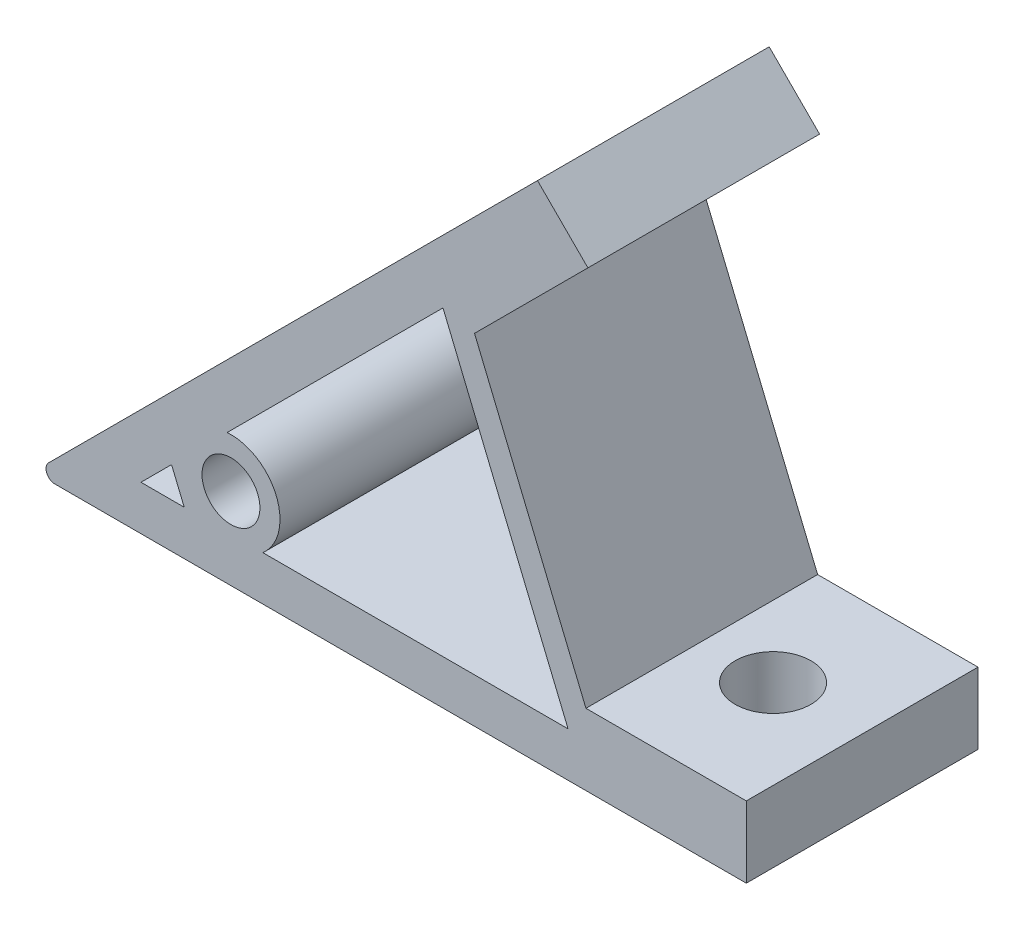
SolidWorks part; units mm, degrees
ref_plane "前视基准面" through (0, 0, 0) normal (0, 0, 1) x (1, 0, 0)
ref_plane "上视基准面" through (0, 0, 0) normal (0, 1, 0) x (1, 0, 0)
ref_plane "右视基准面" through (0, 0, 0) normal (1, 0, 0) x (0, 0, -1)
sketch "草图1" plane through (0, 0, 0) normal (0, 0, 1) x (1, 0, 0)
  line B0 (-77.5858, 0) -> (0, 0)
  line B1 (-67.9289, 5) -> (-63.0745, 5)
  line B2 (-54.2575, 5) -> (-20, 5)
  line B3 (-17.9955, 8) -> (0, 8)
  line B4 (-78.2929, 1.7071) -> (-23.4315, 56.5685)
  line B5 (-67.9289, 5) -> (-64.4963, 8.4326)
  line B6 (-58.2617, 14.6672) -> (-34.0381, 38.8909)
  line B7 (-30.4993, 38.187) -> (-17.7746, 50.9117)
  line B8 (0, 0) -> (0, 8)
  line B9 (-17.7746, 50.9117) -> (-23.4315, 56.5685)
  line B10 (-20, 5) -> (-34.0381, 38.8909)
  line B11 (-17.9955, 8) -> (-30.4993, 38.187)
  line B12 (-63.0745, 5) -> (-64.4963, 8.4326)
  arc B13 (-78.2929, 1.7071) -> (-77.5858, 0) centre (-77.5858, 1) ccw
  circle B14 centre (-57.8269, 9.1844) radius 3.25
  arc B15 (-54.2575, 5) -> (-58.2617, 14.6672) centre (-57.8269, 9.1844) ccw
sketch_block_instance "A$C18907C9D-1"
sketch_block "A$C18907C9D"
extrude "凸台-拉伸1" add sketch "草图1" along normal mid plane 26
sketch "草图3" plane through (0, 8, 0) normal (0, 1, 0) x (1, 0, 0)
  line L0 (0, -13) -> (0, 13) construction
  circle A0 centre (-10, 0) radius 4.25
  dimension "D1" = 10
extrude "切除-拉伸1" cut sketch "草图3" against normal blind 17
sketch "草图4" plane through (-12.5317, -5.1908, 0) normal (0.9239, 0.3827, 0) x (0, 0, -1)
  line L0 (-13, 30.6147) -> (13, 30.6147) construction
  line L1 (-13, 14.2776) -> (-13, 46.9517) construction
  line L2 (13, 14.2776) -> (13, 46.9517) construction
ref_plane "基准面2" through (-11.7157, 28.2843, 0) normal (-0.3827, 0.9239, 0) x (0.9239, 0.3827, 0)
mirror "镜向1" about plane through (-11.7157, 28.2843, 0) normal (-0.3827, 0.9239, 0) of "切除-拉伸1"
